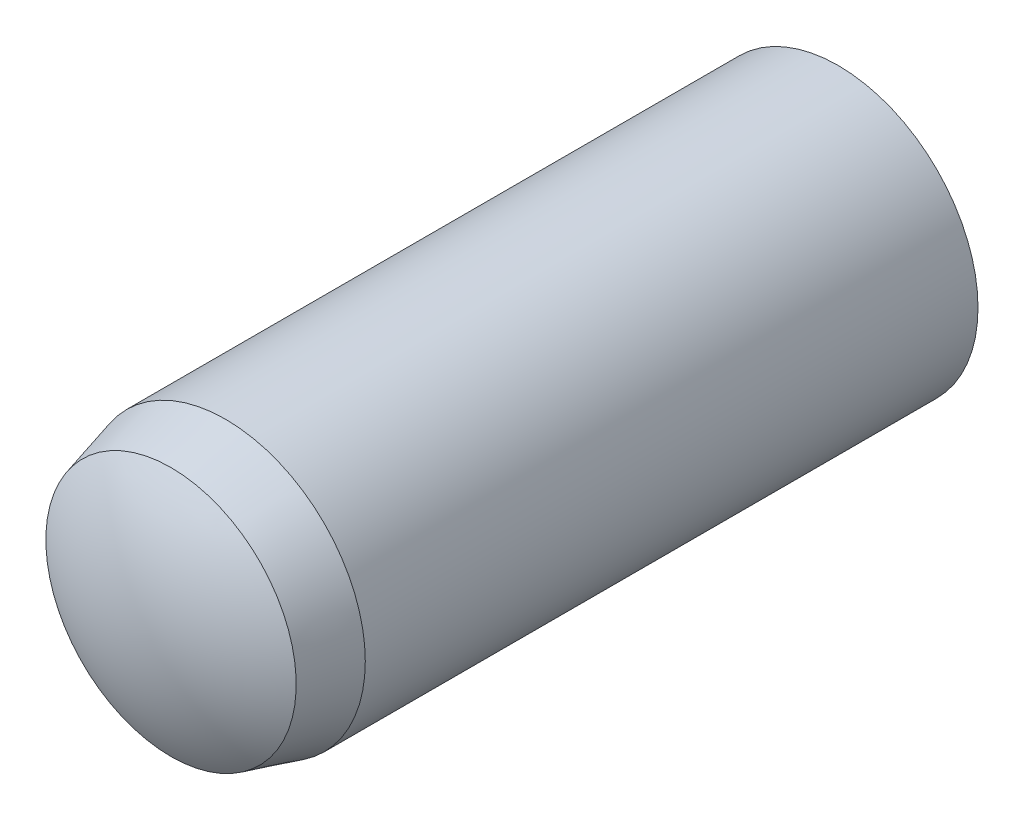
SolidWorks part; units mm, degrees
ref_plane "Front Plane" through (0, 0, 0) normal (0, 0, 1) x (1, 0, 0)
ref_plane "Top Plane" through (0, 0, 0) normal (0, 1, 0) x (1, 0, 0)
ref_plane "Right Plane" through (0, 0, 0) normal (1, 0, 0) x (0, 0, -1)
sketch "Sketch1" plane through (0, 0, 0) normal (0, 0, 1) x (1, 0, 0)
  circle A0 centre (0, 0) radius 1.5
  point P3 (0, 1.5)
  dimension "Diameter" = 3
sketch "Sketch2" plane through (0, 0, 0) normal (1, 0, 0) x (0, 0, -1)
  line L0 (-4, 0) -> (4, 0) construction
  line L1 (-4, 0) -> (-4, 1.5) construction
  line L2 (-4, 1.5) -> (4, 1.5)
  line L3 (4, 1.5) -> (4, 0) construction
  line L4 (-3.61, 1.3432) -> (-3.025, 1.5)
  arc A0 (-4, 0) -> (-3.61, 1.3432) centre (-1.4918, 0) cw
  arc A1 (4, 0) -> (3.55, 1.5) centre (1.275, 0) ccw
  point P2 (0, 0)
  dimension "Length" = 8
  dimension "D1" = 15
  dimension "D2" = 0.45
  dimension "D3" = 0.975
  dimension "D4" = 0.585
sketch "Sketch3" plane through (0, 0, 0) normal (1, 0, 0) x (0, 0, -1)
  line L0 (-4, 0) -> (4, 0) construction
  line L1 (-3.61, 1.3432) -> (-3.025, 1.5) construction
  line L2 (-4, 0) -> (4, 0)
  line L3 (-3.61, 1.3432) -> (-3.025, 1.5)
  line L4 (-3.025, 1.5) -> (3.55, 1.5)
  arc A0 (4, 0) -> (3.55, 1.5) centre (1.275, 0) ccw construction
  arc A1 (-3.61, 1.3432) -> (-4, 0) centre (-1.4918, 0) ccw construction
  arc A2 (4, 0) -> (3.55, 1.5) centre (1.275, 0) ccw
  arc A3 (-3.61, 1.3432) -> (-4, 0) centre (-1.4918, 0) ccw
revolve "Revolve1" add sketch "Sketch3" angle 360 about L2
equation "\"D2@Sketch2\" = \"Diameter@Sketch1\" * .15"
equation "\"D3@Sketch2\" = \"Diameter@Sketch1\" * .325"
equation "\"D4@Sketch2\" = \"D3@Sketch2\" * .6"
